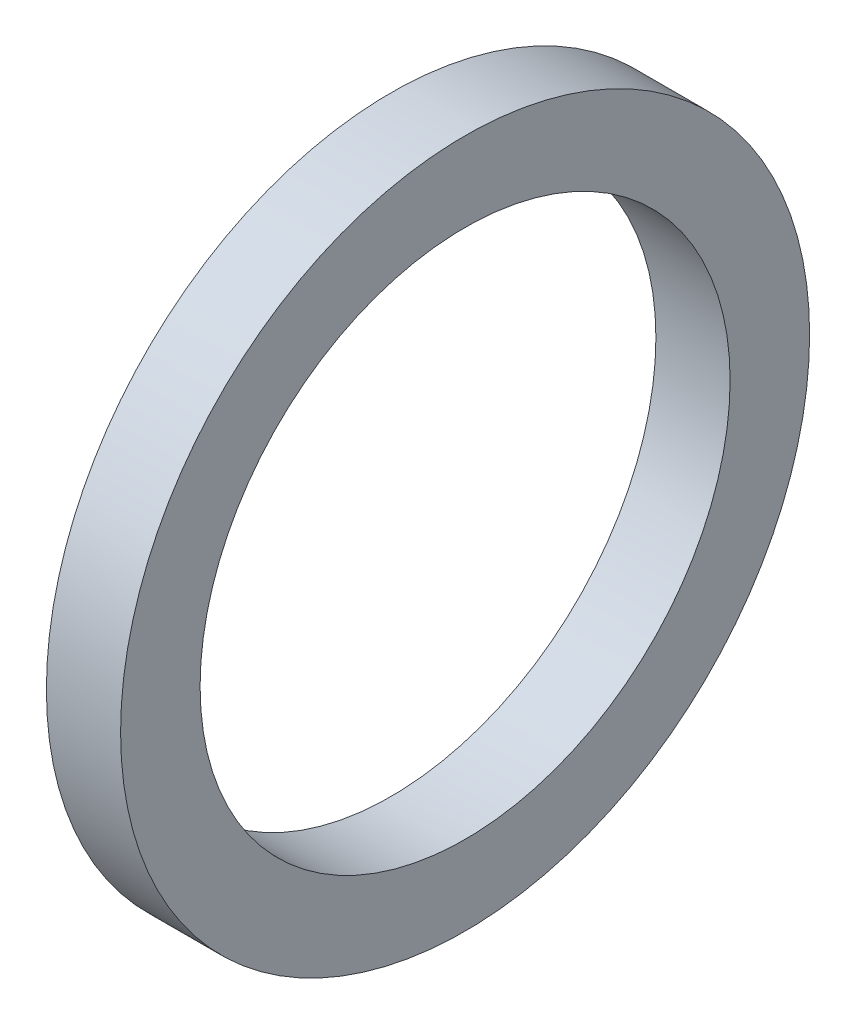
SolidWorks part; units mm, degrees
ref_plane "前视基准面" through (0, 0, 0) normal (0, 0, 1) x (1, 0, 0)
ref_plane "上视基准面" through (0, 0, 0) normal (0, 1, 0) x (1, 0, 0)
ref_plane "右视基准面" through (0, 0, 0) normal (1, 0, 0) x (0, 0, -1)
other "Configuration Table"
sketch "草图1" plane through (0, 0, 0) normal (1, 0, 0) x (0, 0, -1)
  circle A0 centre (0, 0) radius 25
  circle A1 centre (0, 0) radius 32.5
  dimension "D1" = 50
  dimension "D2" = 7.5
extrude "凸台-拉伸1" add sketch "草图1" along normal blind 7
